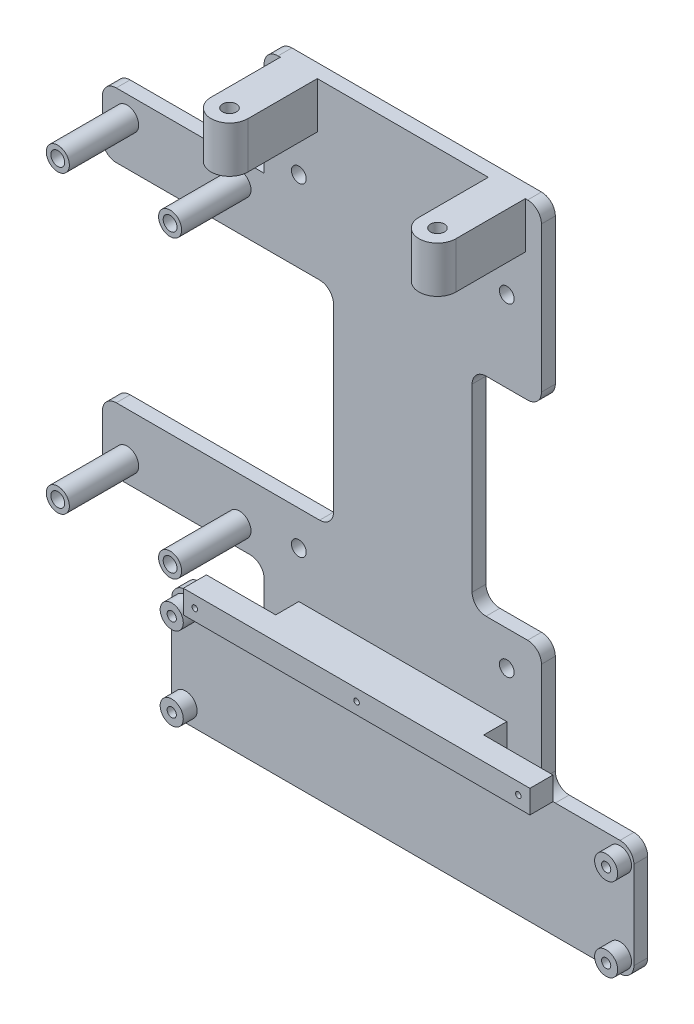
SolidWorks part; units mm, degrees
ref_plane "前视基准面" through (0, 0, 0) normal (0, 0, 1) x (1, 0, 0)
ref_plane "上视基准面" through (0, 0, 0) normal (0, 1, 0) x (1, 0, 0)
ref_plane "右视基准面" through (0, 0, 0) normal (1, 0, 0) x (0, 0, -1)
other "Configuration Table"
sketch "草图1" plane through (0, 0, 0) normal (0, 0, 1) x (1, 0, 0)
  line L1 (0, 0) -> (60, 0)
  line L2 (0, 0) -> (0, 100)
  line L3 (0, 100) -> (60, 100)
  line L4 (60, 0) -> (60, 100)
  dimension "D1" = 100
  dimension "D2" = 60
extrude "凸台-拉伸1" add sketch "草图1" along normal blind 3
sketch "草图2" plane through (0, 0, 3) normal (0, 0, 1) x (1, 0, 0)
  line L0 (30, 100) -> (30, -49900) construction
  line L1 (60, 100) -> (0, 100) construction
  line L3 (7.5, 90) -> (52.5, 90) construction
  line L4 (7.5, 90) -> (7.5, 20) construction
  line L5 (7.5, 20) -> (52.5, 20) construction
  line L6 (52.5, 90) -> (52.5, 20) construction
  circle A0 centre (7.5, 90) radius 1.6
  circle A1 centre (52.5, 90) radius 1.6
  circle A2 centre (52.5, 20) radius 1.6
  circle A3 centre (7.5, 20) radius 1.6
  point P4 (30, 100)
  point P9 (30, 90)
  dimension "D4" = 3.2
  dimension "D5" = 3.2
  dimension "D6" = 3.2
  dimension "D7" = 3.2
  dimension "D1" = 70
  dimension "D2" = 45
  dimension "D3" = 10
extrude "切除-拉伸1" cut sketch "草图2" against normal up to next
sketch "草图3" plane through (0, 0, 3) normal (0, 0, 1) x (1, 0, 0)
  line L0 (30, 0) -> (30, -50000) construction
  line L1 (0, 0) -> (60, 0) construction
  line L3 (-20, 0) -> (80, 0)
  line L4 (-20, 0) -> (-20, -25)
  line L5 (-20, -25) -> (80, -25)
  line L6 (80, 0) -> (80, -25)
  point P4 (30, 0)
  point P10 (30, 0)
  dimension "D1" = 100
  dimension "D2" = 25
extrude "凸台-拉伸2" add sketch "草图3" against normal blind 3
sketch "草图4" plane through (0, 0, 3) normal (0, 0, 1) x (1, 0, 0)
  line L0 (-25, -12.5) -> (49975, -12.5) construction
  line L1 (-20, 0) -> (-20, -25) construction
  line L2 (30, -30) -> (30, 49970) construction
  line L3 (-20, -25) -> (80, -25) construction
  line L5 (-17, -3.5) -> (77, -3.5) construction
  line L6 (-17, -3.5) -> (-17, -21.5) construction
  line L7 (-17, -21.5) -> (77, -21.5) construction
  line L8 (77, -3.5) -> (77, -21.5) construction
  circle A0 centre (-17, -3.5) radius 2.5
  circle A1 centre (-17, -21.5) radius 2.5
  circle A2 centre (77, -21.5) radius 2.5
  circle A3 centre (77, -3.5) radius 2.5
  point P4 (-20, -12.5)
  point P9 (30, -25)
  point P14 (30, -3.5)
  point P15 (-17, -12.5)
  dimension "D3" = 5
  dimension "D4" = 5
  dimension "D5" = 5
  dimension "D6" = 5
  dimension "D1" = 18
  dimension "D2" = 94
extrude "凸台-拉伸3" add sketch "草图4" along normal blind 3
sketch "草图5" plane through (0, 0, 6) normal (0, 0, 1) x (1, 0, 0)
  circle A0 centre (-17, -3.5) radius 1
  circle A1 centre (-17, -21.5) radius 1
  circle A2 centre (77, -21.5) radius 1
  circle A3 centre (77, -3.5) radius 1
  dimension "D1" = 2
  dimension "D2" = 2
  dimension "D3" = 2
  dimension "D4" = 2
extrude "切除-拉伸2" cut sketch "草图5" against normal through all
sketch "草图6" plane through (0, 0, 3) normal (0, 0, 1) x (1, 0, 0)
  line L0 (30, 100) -> (30, -49900) construction
  line L1 (60, 100) -> (0, 100) construction
  line L3 (7.5, 10) -> (52.5, 10)
  line L4 (7.5, 10) -> (7.5, 5)
  line L5 (7.5, 5) -> (52.5, 5)
  line L6 (52.5, 10) -> (52.5, 5)
  line L7 (0, 0) -> (-20, 0) construction
  point P4 (30, 100)
  point P9 (30, 10)
  dimension "D1" = 5
  dimension "D2" = 5
  dimension "45" = 45
extrude "凸台-拉伸4" add sketch "草图6" along normal blind 5
sketch "草图7" plane through (0, 0, 8) normal (0, 0, 1) x (1, 0, 0)
  line L0 (30, 5) -> (30, 50005) construction
  line L1 (52.5, 10) -> (7.5, 10) construction
  line L2 (52.5, 10) -> (7.5, 10) construction
  line L3 (-7.5, 10) -> (67.5, 10)
  line L4 (-7.5, 10) -> (-7.5, 5)
  line L5 (-7.5, 5) -> (67.5, 5)
  line L6 (67.5, 10) -> (67.5, 5)
  line L7 (7.5, 5) -> (52.5, 5) construction
  point P4 (30, 10)
  point P9 (30, 10)
  dimension "D1" = 75
extrude "凸台-拉伸5" add sketch "草图7" along normal blind 5
sketch "草图8" plane through (0, 0, 13) normal (0, 0, 1) x (1, 0, 0)
  line L0 (30, 10) -> (30, -49990) construction
  line L1 (52.5, 10) -> (7.5, 10) construction
  line L2 (-7.5, 7.5) -> (49992.5, 7.5) construction
  line L3 (-7.5, 10) -> (-7.5, 5) construction
  line L4 (65, 7.5) -> (-5, 7.5) construction
  circle A0 centre (-5, 7.5) radius 0.6
  circle A1 centre (30, 7.5) radius 0.6
  circle A2 centre (65, 7.5) radius 0.6
  point P4 (30, 10)
  point P9 (-7.5, 7.5)
  point P13 (30, 7.5)
  dimension "D2" = 1.2
  dimension "D3" = 1.2
  dimension "D4" = 1.2
  dimension "D1" = 70
extrude "切除-拉伸3" cut sketch "草图8" against normal up to surface (5 mm away) up to face at (0, 7.5, 8)
sketch "草图9" plane through (0, 0, 3) normal (0, 0, 1) x (1, 0, 0)
  line L0 (0, 50) -> (-50000, 50) construction
  line L1 (0, 100) -> (0, 0) construction
  line L3 (0, 86.5) -> (-35, 86.5)
  line L4 (0, 86.5) -> (0, 13.5)
  line L5 (0, 13.5) -> (-35, 13.5)
  line L6 (-35, 86.5) -> (-35, 13.5)
  point P4 (0, 50)
  point P10 (0, 50)
  dimension "D1" = 35
  dimension "D2" = 73
extrude "凸台-拉伸6" add sketch "草图9" against normal up to surface (3 mm away) up to face at (78, -3.5, 0)
sketch "草图10" plane through (0, 0, 3) normal (0, 0, 1) x (1, 0, 0)
  line L0 (-35, 50) -> (-50035, 50) construction
  line L1 (-35, 86.5) -> (-35, 13.5) construction
  line L2 (-17.5, 86.5) -> (-17.5, -49913.5) construction
  line L3 (0, 86.5) -> (-35, 86.5) construction
  line L5 (-29.65, 81.95) -> (-5.35, 81.95) construction
  line L6 (-29.65, 81.95) -> (-29.65, 18.05) construction
  line L7 (-29.65, 18.05) -> (-5.35, 18.05) construction
  line L8 (-5.35, 81.95) -> (-5.35, 18.05) construction
  circle A0 centre (-29.65, 81.95) radius 2.5
  circle A1 centre (-5.35, 81.95) radius 2.5
  circle A2 centre (-5.35, 18.05) radius 2.5
  circle A3 centre (-29.65, 18.05) radius 2.5
  point P4 (-35, 50)
  point P9 (-17.5, 86.5)
  point P14 (-17.5, 81.95)
  point P15 (-29.65, 50)
  dimension "D3" = 5
  dimension "D4" = 5
  dimension "D5" = 5
  dimension "D6" = 5
  dimension "D1" = 63.9
  dimension "D2" = 24.3
extrude "凸台-拉伸7" add sketch "草图10" along normal blind 15
sketch "草图11" plane through (0, 0, 18) normal (0, 0, 1) x (1, 0, 0)
  circle A0 centre (-29.65, 81.95) radius 1.5
  circle A1 centre (-5.35, 81.95) radius 1.5
  circle A2 centre (-5.35, 18.05) radius 1.5
  circle A3 centre (-29.65, 18.05) radius 1.5
  dimension "D1" = 3
  dimension "D2" = 3
  dimension "D3" = 3
  dimension "D4" = 3
extrude "切除-拉伸4" cut sketch "草图11" against normal blind 10
sketch "草图12" plane through (0, 0, 0) normal (0, 0, -1) x (-1, 0, 0)
  line L0 (-30, 100) -> (-30, -49900) construction
  line L1 (-60, 100) -> (0, 100) construction
  line L3 (-60, 110) -> (0, 110)
  line L4 (-60, 110) -> (-60, 100)
  line L5 (-60, 100) -> (0, 100)
  line L6 (0, 110) -> (0, 100)
  point P4 (-30, 100)
  point P10 (-30, 110)
  dimension "D1" = 10
  dimension "D2" = 60
extrude "凸台-拉伸8" add sketch "草图12" against normal blind 28
sketch "草图13" plane through (0, 100, 0) normal (0, -1, 0) x (1, 0, 0)
  line L0 (30, 28) -> (30, -49972) construction
  line L1 (7.5, 18) -> (52.5, 18) construction
  line L2 (3.5, 18) -> (3.5, 3)
  line L3 (11.5, 18) -> (11.5, 3)
  line L4 (0, 3) -> (60, 3)
  line L5 (60, 3) -> (60, 28)
  line L6 (60, 28) -> (0, 28)
  line L7 (0, 28) -> (0, 3)
  line L8 (0, 3) -> (60, 3)
  line L9 (60, 3) -> (60, 28)
  line L10 (60, 28) -> (0, 28)
  line L11 (0, 28) -> (0, 3)
  line L12 (48.5, 18) -> (48.5, 3)
  line L13 (56.5, 18) -> (56.5, 3)
  circle A0 centre (7.5, 18) radius 4
  circle A1 centre (52.5, 18) radius 4
  point P6 (30, 28)
  point P10 (30, 18)
  line M8 (0, 3) -> (60, 3)
  line M9 (60, 3) -> (60, 28)
  line M10 (60, 28) -> (0, 28)
  line M11 (0, 28) -> (0, 3)
  dimension "D4" = 8
  dimension "D2" = 45
  dimension "D3" = 15
  dimension "D1" = 0
extrude "切除-拉伸5" cut sketch "草图13" against normal up to next contours L12 A1 L13 L2 A0 L3 M8 M9 M10 M11
sketch "草图14" plane through (0, 110, 0) normal (0, 1, 0) x (1, 0, 0)
  circle A0 centre (7.5, -18) radius 1.5
  circle A1 centre (52.5, -18) radius 1.5
  dimension "D1" = 3
  dimension "D2" = 3
extrude "切除-拉伸6" cut sketch "草图14" against normal up to next
sketch "草图15" plane through (0, 0, 3) normal (0, 0, 1) x (1, 0, 0)
  line L0 (-35, 50) -> (-50035, 50) construction
  line L1 (-35, 86.5) -> (-35, 13.5) construction
  line L2 (30, 110) -> (30, -49890) construction
  line L3 (-35, 72.5) -> (15, 72.5)
  line L4 (-35, 72.5) -> (-35, 27.5)
  line L5 (-35, 27.5) -> (15, 27.5)
  line L6 (15, 72.5) -> (15, 27.5)
  line L8 (11.5, 110) -> (48.5, 110) construction
  line L9 (45, 72.5) -> (45, 27.5)
  line L10 (45, 72.5) -> (60, 72.5)
  line L11 (60, 0) -> (60, 110) construction
  line L12 (60, 72.5) -> (60, 27.5)
  line L13 (60, 27.5) -> (45, 27.5)
  point P4 (-35, 50)
  point P9 (-35, 50)
  point P15 (30, 110)
  dimension "D1" = 30
  dimension "D2" = 45
extrude "切除-拉伸7" cut sketch "草图15" against normal up to next
fillet "圆角1" radius 3 1 edges at (15, 27.5, 1.5)
fillet "圆角2" radius 3 1 edges at (15, 72.5, 1.5)
fillet "圆角3" radius 3 1 edges at (-35, 86.5, 1.5)
fillet "圆角4" radius 3 1 edges at (-35, 72.5, 1.5)
fillet "圆角5" radius 3 1 edges at (0, 110, 1.5)
fillet "圆角6" radius 3 14 edges at (60, 110, 1.5) (60, 72.5, 1.5) (45, 72.5, 1.5) (45, 27.5, 1.5) (60, 27.5, 1.5) (60, 0, 1.5) (80, 0, 1.5) (80, -25, 1.5) (-20, -25, 1.5) (-20, 0, 1.5) (0, 0, 1.5) (0, 13.5, 1.5) (-35, 13.5, 1.5) (-35, 27.5, 1.5)
